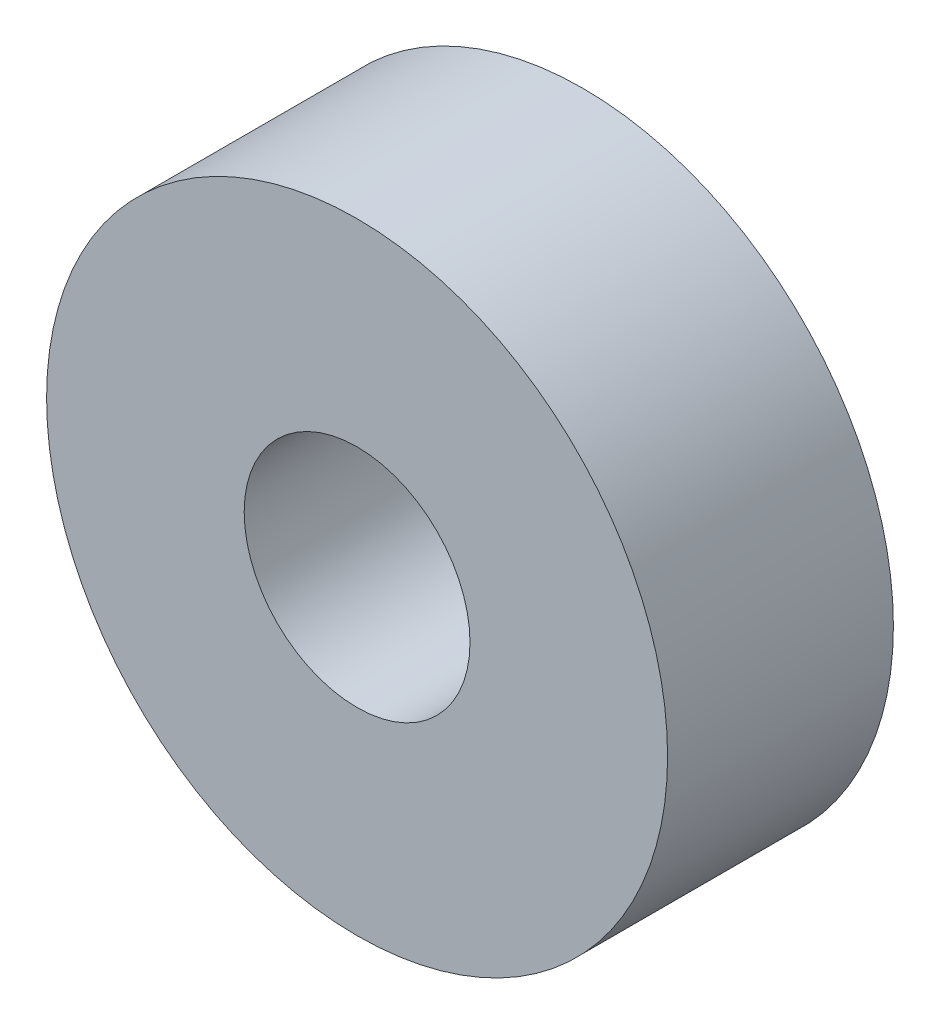
SolidWorks part; units mm, degrees
ref_plane "Front Plane" through (0, 0, 0) normal (0, 0, 1) x (1, 0, 0)
ref_plane "Top Plane" through (0, 0, 0) normal (0, 1, 0) x (1, 0, 0)
ref_plane "Right Plane" through (0, 0, 0) normal (1, 0, 0) x (0, 0, -1)
sketch "Sketch1" plane through (0, 0, 0) normal (0, 0, 1) x (1, 0, 0)
  circle A0 centre (0, 0) radius 11
  circle A1 centre (0, 0) radius 4
  dimension "D1" = 22
  dimension "D2" = 8
extrude "Boss-Extrude1" add sketch "Sketch1" along normal blind 8
